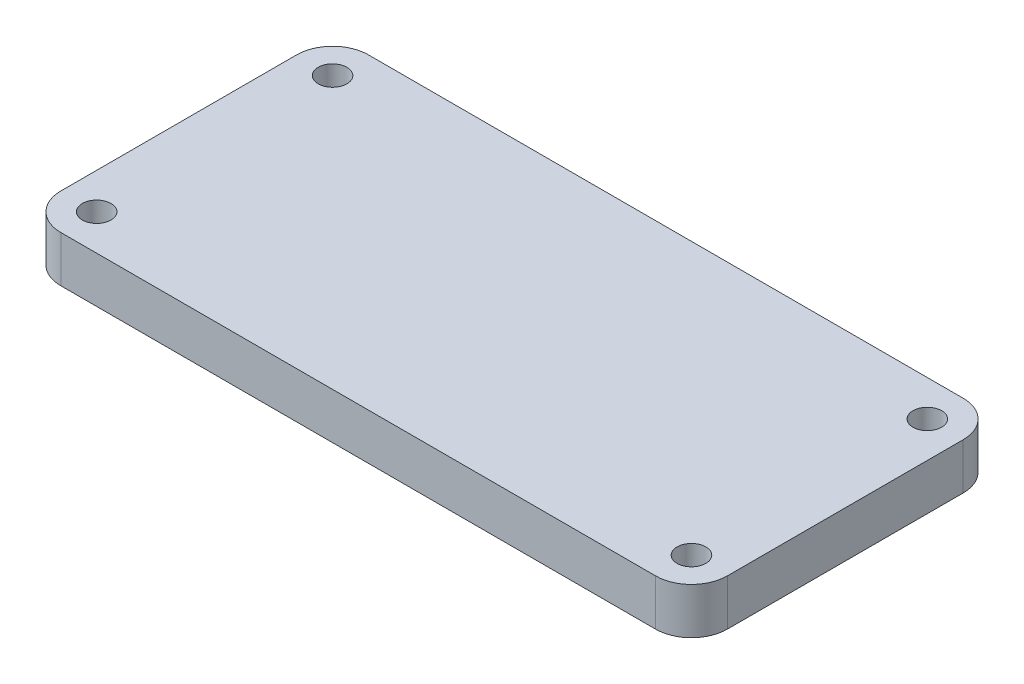
SolidWorks part; units mm, degrees
ref_plane "前视基准面" through (0, 0, 0) normal (0, 0, 1) x (1, 0, 0)
ref_plane "上视基准面" through (0, 0, 0) normal (0, 1, 0) x (1, 0, 0)
ref_plane "右视基准面" through (0, 0, 0) normal (1, 0, 0) x (0, 0, -1)
other "Configuration Table"
sketch "草图1" plane through (0, 0, 0) normal (0, 1, 0) x (1, 0, 0)
  line L1 (-29, -15) -> (29, -15)
  line L2 (-32.5, -11.5) -> (-32.5, 11.5)
  line L3 (-29, 15) -> (29, 15)
  line L4 (32.5, -11.5) -> (32.5, 11.5)
  line L5 (-32.5, -15) -> (32.5, 15) construction
  line L6 (-32.5, 15) -> (32.5, -15) construction
  arc A0 (29, -15) -> (32.5, -11.5) centre (29, -11.5) ccw
  arc A1 (29, 15) -> (32.5, 11.5) centre (29, 11.5) cw
  arc A2 (-32.5, 11.5) -> (-29, 15) centre (-29, 11.5) cw
  arc A3 (-29, -15) -> (-32.5, -11.5) centre (-29, -11.5) cw
  circle A4 centre (-29, -11.5) radius 1.4
  circle A5 centre (-29, 11.5) radius 1.4
  circle A6 centre (29, 11.5) radius 1.4
  circle A7 centre (29, -11.5) radius 1.4
  point P0 (0, 0)
  dimension "D3" = 3.5
  dimension "D4" = 3.5
  dimension "D5" = 3.5
  dimension "D6" = 3.5
  dimension "D1" = 65
  dimension "D2" = 30
extrude "凸台-拉伸1" add sketch "草图1" along normal blind 4.5
